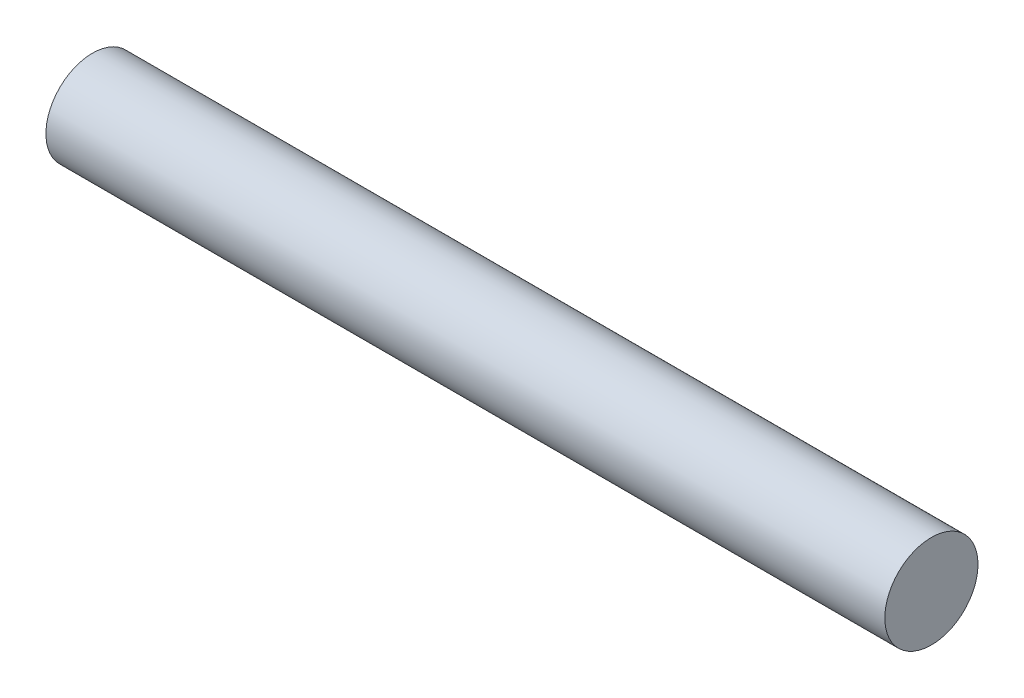
SolidWorks part; units mm, degrees
material "Plain Carbon Steel"
ref_plane "Front Plane" through (0, 0, 0) normal (0, 0, 1) x (1, 0, 0)
ref_plane "Top Plane" through (0, 0, 0) normal (0, 1, 0) x (1, 0, 0)
ref_plane "Right Plane" through (0, 0, 0) normal (1, 0, 0) x (0, 0, -1)
sketch "Sketch1" plane through (0, 0, 0) normal (1, 0, 0) x (0, 0, -1)
  circle A0 centre (0, 0) radius 3.175
  dimension "D1" = 6.35
extrude "Boss-Extrude1" add sketch "Sketch1" along normal blind 57.15
